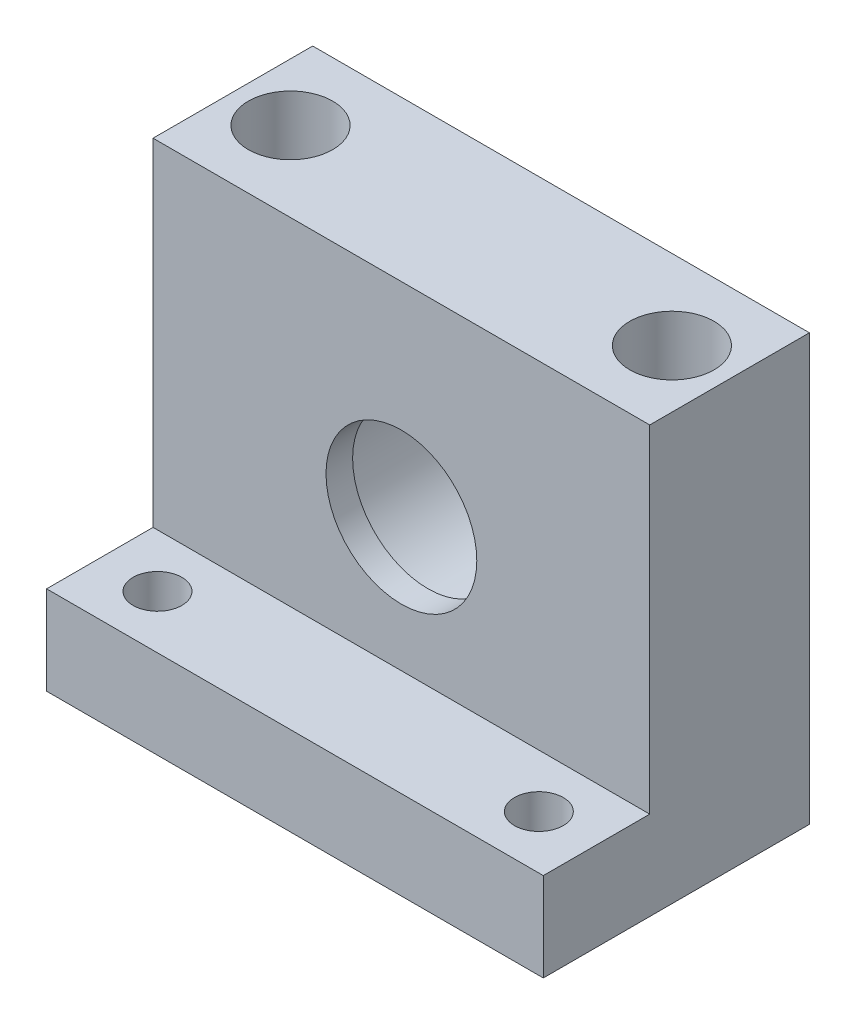
SolidWorks part; units mm, degrees
ref_plane "前视基准面" through (0, 0, 0) normal (0, 0, 1) x (1, 0, 0)
ref_plane "上视基准面" through (0, 0, 0) normal (0, 1, 0) x (1, 0, 0)
ref_plane "右视基准面" through (0, 0, 0) normal (1, 0, 0) x (0, 0, -1)
sketch "草图1" plane through (0, 0, 0) normal (0, 0, 1) x (1, 0, 0)
  line L1 (-28, 24) -> (28, 24)
  line L2 (-28, 24) -> (-28, -24)
  line L3 (-28, -24) -> (28, -24)
  line L4 (28, 24) -> (28, -24)
  line L5 (-28, 24) -> (28, -24) construction
  line L6 (-28, -24) -> (28, 24) construction
  point P0 (0, 0)
  dimension "D1" = 56
  dimension "D2" = 48
extrude "凸台-拉伸1" add sketch "草图1" along normal blind 18
sketch "草图9" plane through (0, 0, 0) normal (0, 0, -1) x (-1, 0, 0)
  line L0 (28, -24) -> (-28, -24) construction
  line L2 (0, 0) -> (0, -3.157) construction
  circle A0 centre (0, 1) radius 11
  dimension "D1" = 22
  dimension "D2" = 25
extrude "切除-拉伸3" cut sketch "草图9" against normal blind 15
sketch "草图10" plane through (0, 0, 15) normal (0, 0, -1) x (-1, 0, 0)
  circle A0 centre (0, 1) radius 8.5
  dimension "D1" = 17
extrude "切除-拉伸4" cut sketch "草图10" against normal blind 17
hole_wizard "M3 螺纹孔2" positions "草图12" profile "草图11" tap size "M3" standard "GB"
sketch "草图12" plane through (0, 0, 0) normal (0, 0, -1) x (-1, 0, 0)
  line L0 (0, 21) -> (0, 0) construction
  line L4 (11, 1) -> (2.7911, 1) construction
  circle A0 centre (0, 1) radius 11 construction
  circle A1 centre (0, 1) radius 11 construction
  point P0 (12, 8)
  point P2 (-12, 8)
  point P4 (12, -6)
  point P6 (-12, -6)
  dimension "D1" = 24
  dimension "D2" = 14
sketch "草图11" plane through (-12, 8, 0) normal (1, 0, 0) x (0, 1, 0)
  line L0 (0, 0) -> (0, 9.2511)
  line L1 (0, 9.2511) -> (1.25, 8.5)
  line L2 (1.25, 8.5) -> (1.25, 0)
  line L5 (1.25, 0) -> (0, 0)
  line L10 (0, 9.2511) -> (-1.25, 8.5) construction
  line L11 (0, -6.35) -> (0, 107.95) construction
  dimension "螺纹孔钻头直径" = 2.5
  dimension "螺纹孔钻头深度" = 8.5
  dimension "导头角度" = 118
cosmetic thread "孔螺蚊线17" parameters "D1"=6, "D2"=3
cosmetic thread "孔螺蚊线18" parameters "D1"=6, "D2"=3
cosmetic thread "孔螺蚊线19" parameters "D1"=6, "D2"=3
cosmetic thread "孔螺蚊线20" parameters "D1"=6, "D2"=3
hole_wizard "M5 六角头螺栓的柱形沉头孔1" positions "草图16" profile "草图15" counterbore size "M5" standard "GB" end condition through all
sketch "草图16" plane through (-28, 24, 18.0392) normal (0, 1, 0) x (1, 0, 0)
  line L0 (-27.5, 9.0392) -> (56, 9.0392) construction
  line L4 (28, 18.0392) -> (28, 9.0785) construction
  line L5 (56, 0.0392) -> (56, 18.0392) construction
  point P0 (6.5, 9.0392)
  point P2 (49.5, 9.0392)
  dimension "D1" = 43
sketch "草图15" plane through (-21.5, 24, 9) normal (1, 0, 0) x (0, 0, 1)
  line L0 (0, 0) -> (0, 48)
  line L1 (0, 48) -> (2.75, 48)
  line L3 (2.75, 48) -> (2.75, 30)
  line L4 (2.75, 30) -> (4.75, 30)
  line L5 (4.75, 30) -> (4.75, 0)
  line L7 (4.75, 0) -> (0, 0)
  line L11 (0, -6.35) -> (0, 107.95) construction
  dimension "通孔孔直径" = 5.5
  dimension "通孔孔深度" = 48
  dimension "柱形沉头孔直径" = 9.5
  dimension "柱形沉头孔深度" = 30
sketch "草图17" plane through (0, 0, 18) normal (0, 0, 1) x (1, 0, 0)
  line L1 (-28, -24) -> (28, -24)
  line L2 (-28, -24) -> (-28, -14)
  line L3 (-28, -14) -> (28, -14)
  line L4 (28, -24) -> (28, -14)
  line L6 (-28, -24) -> (28, -24) construction
  line L7 (28, -24) -> (28, 24) construction
  line L8 (-28, 24) -> (-28, -24) construction
  dimension "D1" = 10
extrude "凸台-拉伸5" add sketch "草图17" along normal blind 12
hole_wizard "Ø5.5 (5.5) 直径孔1" positions "草图19" profile "草图20" hole size "Ø5.5" standard "GB"
sketch "草图19" plane through (0, -14, 0) normal (0, 1, 0) x (1, 0, 0)
  line L0 (0, -18) -> (0, 0) construction
  line L2 (28, -18) -> (-28, -18) construction
  point P0 (-21.5, -24)
  point P2 (21.5, -24)
  dimension "D1" = 43
  dimension "D2" = 6
sketch "草图20" plane through (-21.5, -14, 24) normal (1, 0, 0) x (0, 0, 1)
  line L0 (0, 0) -> (0, 10)
  line L1 (0, 10) -> (2.75, 10)
  line L2 (2.75, 10) -> (2.75, 0)
  line L5 (2.75, 0) -> (0, 0)
  line L10 (0, 10) -> (-2.75, 10) construction
  line L11 (0, -6.35) -> (0, 107.95) construction
  dimension "孔直径" = 5.5
  dimension "孔深度" = 10
  dimension "导头角度" = 180
sketch "草图21" plane through (0, 0, 0) normal (0, 0, -1) x (-1, 0, 0)
  line L0 (0, 24) -> (0, 0) construction
  line L1 (-28, 24) -> (28, 24) construction
  circle A0 centre (-12.5, 19) radius 3
  circle A1 centre (12.5, 19) radius 3
  dimension "D1" = 6
  dimension "D2" = 25
  dimension "D3" = 5
extrude "切除-拉伸5" cut sketch "草图21" against normal blind 8
